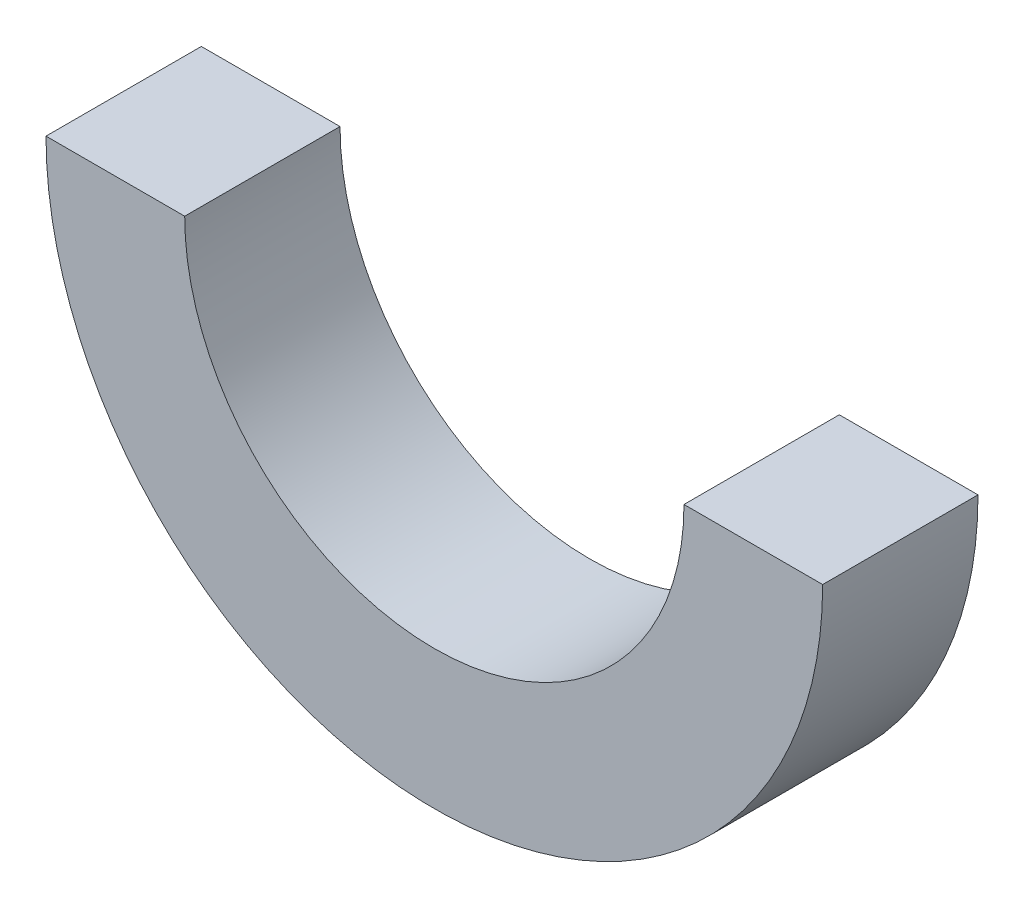
SolidWorks part; units mm, degrees
ref_plane "정면" through (0, 0, 0) normal (0, 0, 1) x (1, 0, 0)
ref_plane "윗면" through (0, 0, 0) normal (0, 1, 0) x (1, 0, 0)
ref_plane "우측면" through (0, 0, 0) normal (1, 0, 0) x (0, 0, -1)
sketch "스케치1" plane through (0, 0, 0) normal (0, 0, 1) x (1, 0, 0)
  line L0 (-17.5, 0) -> (17.5, 0)
  arc A0 (-17.5, 0) -> (17.5, 0) centre (0, 0) ccw
  arc A1 (-11.25, 0) -> (11.25, 0) centre (0, 0) ccw
  dimension "D1" = 35
  dimension "D2" = 22.5
extrude "보스-돌출1" add sketch "스케치1" along normal blind 7 contours A1 L0 A0
